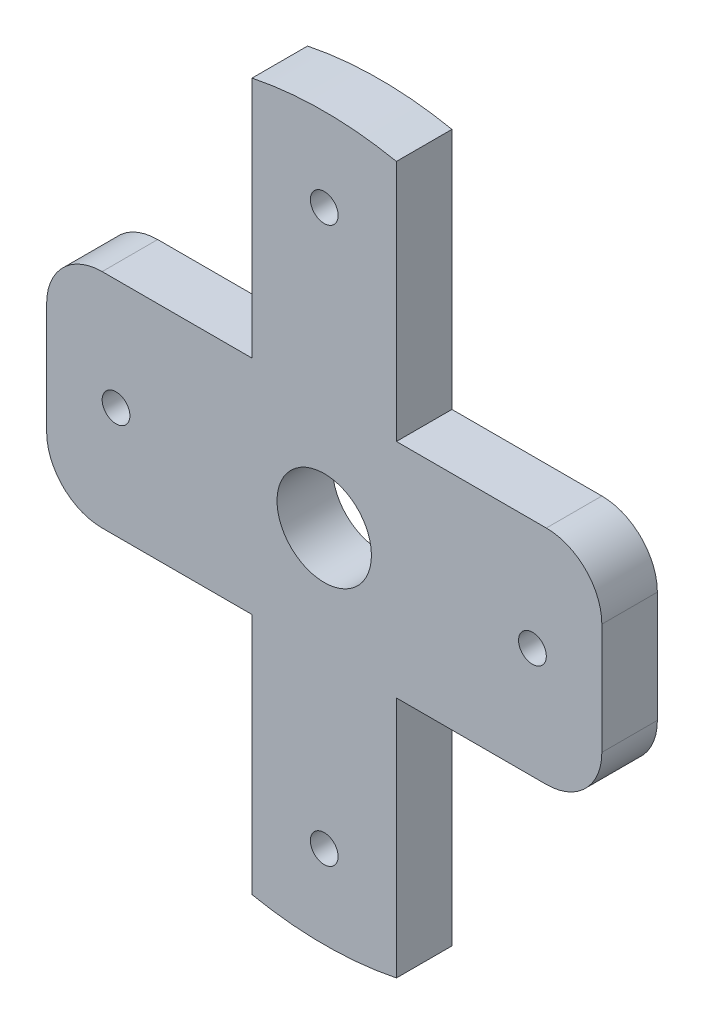
SolidWorks part; units mm, degrees
ref_plane "Front Plane" through (0, 0, 0) normal (0, 0, 1) x (1, 0, 0)
ref_plane "Top Plane" through (0, 0, 0) normal (0, 1, 0) x (1, 0, 0)
ref_plane "Right Plane" through (0, 0, 0) normal (1, 0, 0) x (0, 0, -1)
sketch "Sketch1" plane through (0, 0, 0) normal (0, 0, 1) x (1, 0, 0)
  line L0 (-13, 20) -> (-40, 20)
  line L1 (-50, 10) -> (-50, -10)
  line L2 (-40, -20) -> (-13, -20)
  line L3 (13, 20) -> (40, 20)
  line L4 (13, -20) -> (40, -20)
  line L5 (-13, -20) -> (-13, -63.6867)
  line L6 (13, -20) -> (13, -63.6867)
  line L7 (-13, 20) -> (-13, 63.6867)
  line L8 (13, 20) -> (13, 63.6867)
  line L9 (50, 10) -> (50, -10)
  arc A0 (-13, -63.6867) -> (13, -63.6867) centre (0, 0) ccw
  circle A1 centre (-37.5, 0) radius 2.5
  circle A2 centre (0, -50) radius 2.5
  circle A3 centre (37.5, 0) radius 2.5
  circle A4 centre (0, 50) radius 2.5
  circle A6 centre (0, 0) radius 8.5
  arc A7 (40, 20) -> (50, 10) centre (40, 10) cw
  arc A8 (50, -10) -> (40, -20) centre (40, -10) cw
  arc A9 (-50, -10) -> (-40, -20) centre (-40, -10) ccw
  arc A10 (-40, 20) -> (-50, 10) centre (-40, 10) ccw
  arc A11 (13, 63.6867) -> (-13, 63.6867) centre (0, 0) ccw
  point P6 (0, 0)
  point P22 (0, 0)
  point P29 (0, 0)
  dimension "D1" = 5
  dimension "D2" = 5
  dimension "D3" = 5
  dimension "D4" = 5
  dimension "D5" = 10
  dimension "D6" = 10
  dimension "D7" = 10
  dimension "D8" = 10
extrude "Boss-Extrude1" add sketch "Sketch1" along normal blind 10
